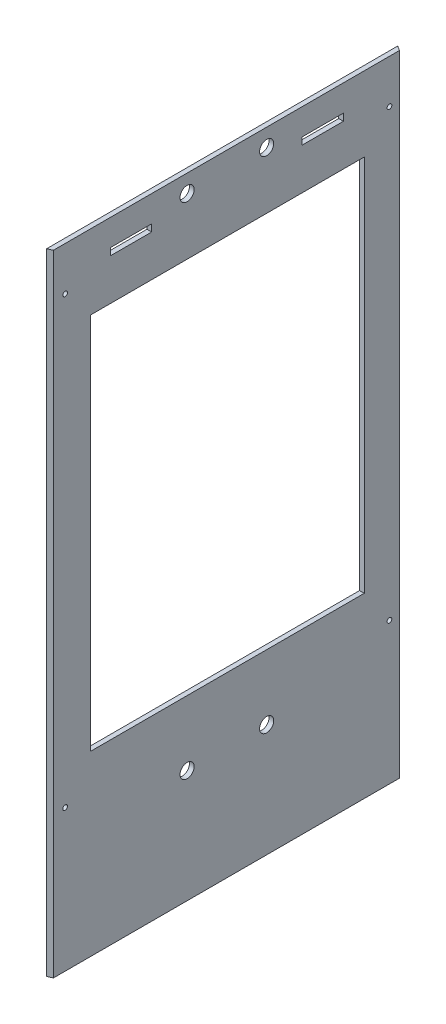
SolidWorks part; units mm, degrees
ref_plane "Спереди" through (0, 0, 0) normal (0, 0, 1) x (1, 0, 0)
ref_plane "Сверху" through (0, 0, 0) normal (0, 1, 0) x (1, 0, 0)
ref_plane "Справа" through (0, 0, 0) normal (1, 0, 0) x (0, 0, -1)
sketch "Эскиз1" plane through (0, 0, 0) normal (0, 1, 0) x (1, 0, 0)
  line L0 (4.0186, 1.7475) -> (79.181, -66.868) construction
  line L1 (0, 0) -> (4, 1.7645)
  line L2 (0, 0) -> (0, 297.3876)
  line L3 (0, 297.3876) -> (4, 294.8273)
  line L4 (4, 1.7645) -> (4, 294.8273)
  dimension "D1" = 4
extrude "Вытянуть1" add sketch "Эскиз1" along normal up to surface (533.7137 mm away)
sketch "Эскиз2" plane through (0, 0, 0) normal (-1, 0, 0) x (0, 0, 1)
  line L0 (-272.3275, 260.902) -> (-272.3275, -22.3628)
  line L1 (-272.3275, 260.902) -> (-25.1909, 260.902)
  line L3 (-272.3275, -22.3628) -> (-25.1909, -22.3628)
  line L4 (-25.1909, 260.902) -> (-25.1909, -22.3628)
  line L6 (-264.3275, 152.3571) -> (-192.5685, 152.3571) construction
sketch "Sketch1" plane through (0, 0, 0) normal (-1, 0, 0) x (0, 0, 1)
  line L0 (-149.0559, 533.7137) -> (-149.0559, 365.9424) construction
  line L2 (-466.2387, 150.5) -> (190.429, 150.5) construction
  line L3 (-297.6324, 0.5) -> (0.0403, 0.5) construction
  line L4 (-507.1548, 470.5) -> (192.6943, 470.5) construction
  line L5 (-451.9035, 310.5) -> (226.1799, 310.5) construction
  line L7 (-33.0559, 150.5) -> (-265.0559, 150.5)
  line L8 (-33.0559, 150.5) -> (-33.0559, 470.5)
  line L9 (-33.0559, 470.5) -> (-265.0559, 470.5)
  line L10 (-265.0559, 150.5) -> (-265.0559, 470.5)
  line L11 (-33.0559, 150.5) -> (-265.0559, 470.5) construction
  line L12 (-33.0559, 470.5) -> (-265.0559, 150.5) construction
  point P9 (-149.0559, 310.5)
  dimension "D1" = 150
  dimension "D2" = 320
  dimension "D3" = 160
extrude "Cut-Extrude1" cut sketch "Sketch1" against normal through all
sketch "Sketch2" plane through (0, 0, 0) normal (-1, 0, 0) x (0, 0, 1)
  line L0 (-325.7416, 505.5) -> (32.5763, 505.5) construction
  line L1 (-33.0559, 470.5) -> (-265.0559, 470.5) construction
  line L2 (-247.3876, 583.7888) -> (-247.3876, 553.0639) construction
  line L4 (-297.3876, 533.7137) -> (-297.3876, 0) construction
  line L5 (-148.6938, 533.7137) -> (-148.6938, 623.8727) construction
  line L6 (-247.3876, 505.5) -> (-212.3876, 505.5)
  line L7 (-247.3876, 505.5) -> (-247.3876, 511.5)
  line L8 (-247.3876, 511.5) -> (-212.3876, 511.5)
  line L9 (-212.3876, 505.5) -> (-212.3876, 511.5)
  line L11 (-50, 505.5) -> (-50, 511.5)
  line L12 (-50, 505.5) -> (-85, 505.5)
  line L13 (-85, 505.5) -> (-85, 511.5)
  line L14 (-50, 511.5) -> (-85, 511.5)
  dimension "D1" = 35
  dimension "D2" = 50
extrude "Cut-Extrude2" cut sketch "Sketch2" against normal through all
sketch "Sketch3" plane through (0, 0, 0) normal (-1, 0, 0) x (0, 0, 1)
  line L0 (-297.3876, 533.7137) -> (-297.3876, 0) construction
  line L1 (-297.3876, 533.7137) -> (0, 533.7137) construction
  line L2 (0, 533.7137) -> (0, 0) construction
  line L3 (-297.8921, 533.7137) -> (-0.2197, 533.7137) construction
  line L4 (-297.6324, 0.5) -> (0.0403, 0.5) construction
  circle A0 centre (-182.3876, 518.7137) radius 6
  circle A1 centre (-115, 518.7137) radius 6
  circle A2 centre (-182.3876, 95.5) radius 6
  circle A3 centre (-115, 95.5) radius 6
  dimension "D1" = 115
  dimension "D3" = 115
  dimension "D5" = 95
  dimension "D7" = 115
  dimension "D2" = 15
  dimension "D4" = 15
  dimension "D6" = 115
extrude "Cut-Extrude3" cut sketch "Sketch3" against normal through all
sketch "Sketch4" plane through (0, 0, 0) normal (-1, 0, 0) x (0, 0, 1)
  line L0 (-297.8921, 533.7137) -> (-0.2197, 533.7137) construction
  line L1 (-297.3876, 533.7137) -> (-297.3876, 0) construction
  line L2 (-149.0559, 533.7137) -> (-149.0559, 576.7744) construction
  line L3 (-297.3876, 0) -> (0, 0) construction
  circle A0 centre (-286.3876, 496.7137) radius 2
  circle A1 centre (-11.7242, 496.7137) radius 2
  circle A2 centre (-286.3876, 120) radius 2
  circle A3 centre (-11.7242, 120) radius 2
  dimension "D1" = 37
  dimension "D3" = 120
  dimension "D2" = 11
  dimension "D4" = 11
extrude "Cut-Extrude4" cut sketch "Sketch4" against normal through all
